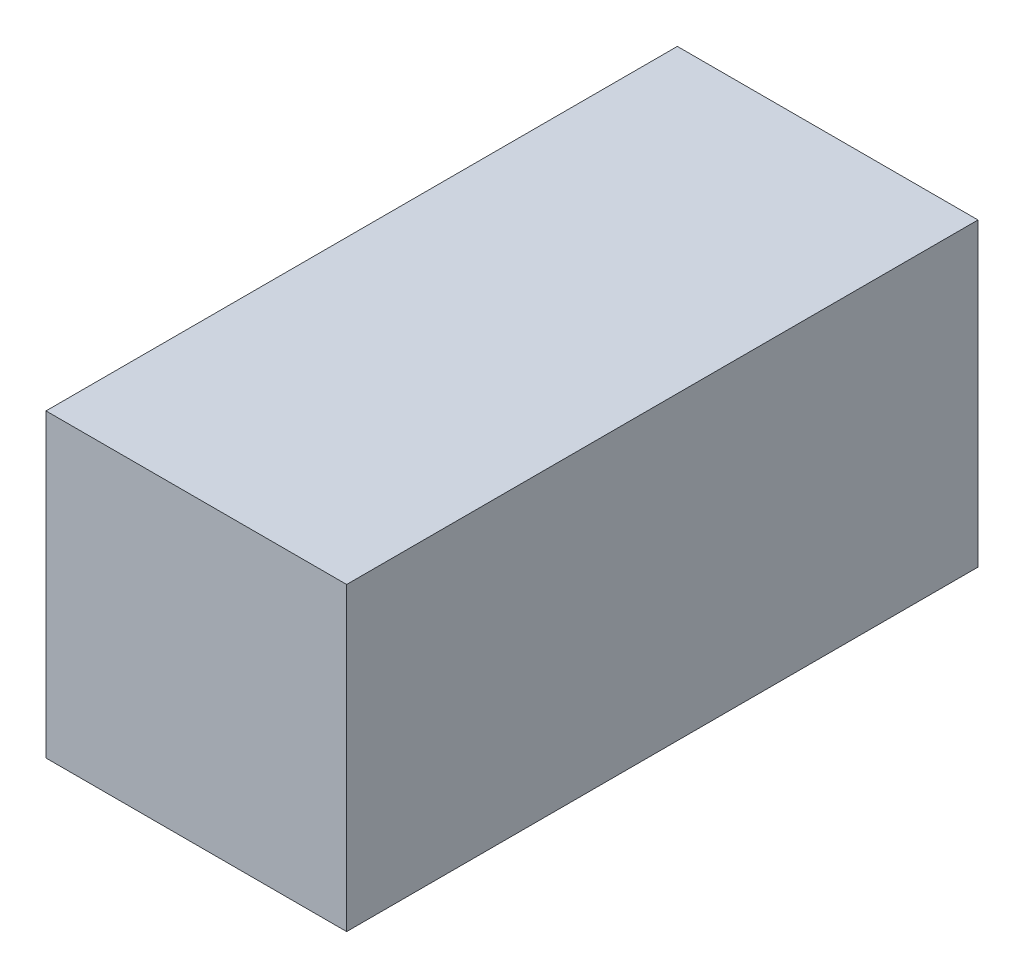
SolidWorks part; units mm, degrees
ref_plane "前视基准面" through (0, 0, 0) normal (0, 0, 1) x (1, 0, 0)
ref_plane "上视基准面" through (0, 0, 0) normal (0, 1, 0) x (1, 0, 0)
ref_plane "右视基准面" through (0, 0, 0) normal (1, 0, 0) x (0, 0, -1)
other "Configuration Table"
sketch "草图1" plane through (0, 0, 0) normal (0, 1, 0) x (1, 0, 0)
  line L1 (-50, 105) -> (50, 105)
  line L2 (-50, 105) -> (-50, -105)
  line L3 (-50, -105) -> (50, -105)
  line L4 (50, 105) -> (50, -105)
  line L5 (-50, 105) -> (50, -105) construction
  line L6 (-50, -105) -> (50, 105) construction
  point P0 (0, 0)
  dimension "D1" = 210
  dimension "D2" = 100
extrude "凸台-拉伸1" add sketch "草图1" along normal mid plane 100
